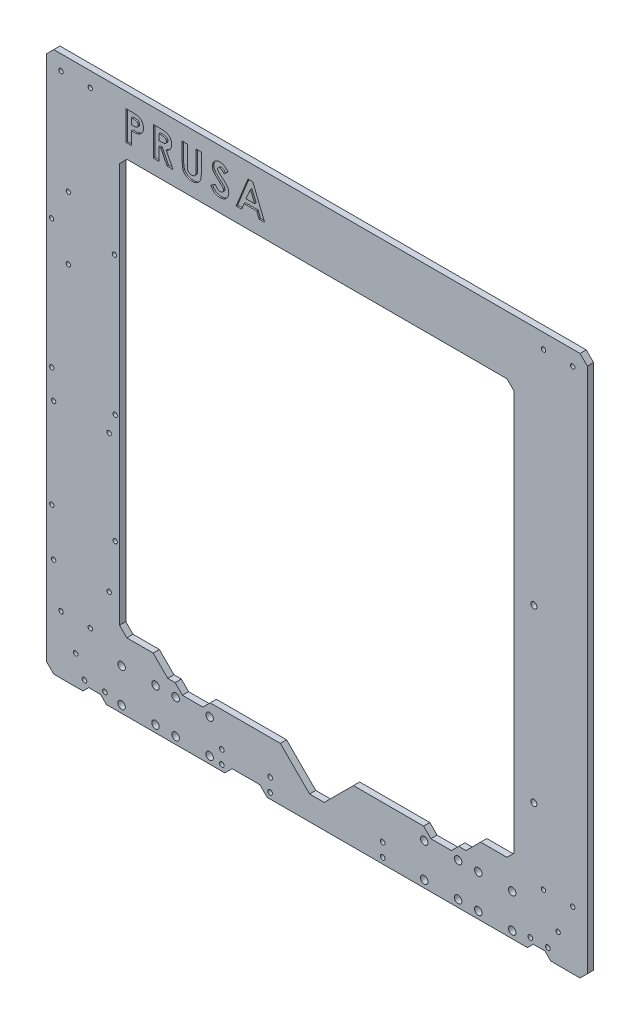
SolidWorks part; units mm, degrees
material "6063-O, Extruded Rod (SS)"
ref_plane "Front Plane" through (0, 0, 0) normal (0, 0, 1) x (1, 0, 0)
ref_plane "Top Plane" through (0, 0, 0) normal (0, 1, 0) x (1, 0, 0)
ref_plane "Right Plane" through (0, 0, 0) normal (1, 0, 0) x (0, 0, -1)
sketch "Sketch1" plane through (0, 0, 0) normal (0, 0, 1) x (1, 0, 0)
  line L0 (162, 177.023) -> (141.977, 157)
  line L1 (141.977, 157) -> (125, 157)
  line L2 (125, 157) -> (101.5, 180.5)
  line L3 (101.5, 189.5) -> (125, 213)
  line L4 (125, 213) -> (141.977, 213)
  line L5 (141.977, 213) -> (162, 192.977)
  line L6 (251.5, 210.0147) -> (240.9853, 220.5294)
  line L7 (240.9853, 220.5294) -> (224.0147, 220.5294)
  line L8 (224.0147, 220.5294) -> (197, 193.5147)
  line L9 (197, 176.4853) -> (224.0147, 149.4706)
  line L10 (224.0147, 149.4706) -> (240.9853, 149.4706)
  line L11 (240.9853, 149.4706) -> (251.5, 159.9853)
  line L12 (184.4001, 296) -> (225.4001, 255)
  line L13 (225.4001, 255) -> (241.5147, 255)
  line L14 (241.5147, 255) -> (282.5147, 296)
  line L15 (282.5147, 296) -> (287.4852, 296)
  line L16 (287.4852, 296) -> (291, 292.4852)
  line L17 (291, 292.4852) -> (291, 287.5147)
  line L18 (291, 287.5147) -> (253, 249.5147)
  line L19 (253, 249.5147) -> (253, 226.667)
  line L20 (253, 226.667) -> (291, 188.667)
  line L21 (291, 188.667) -> (291, 181.333)
  line L22 (291, 181.333) -> (253, 143.333)
  line L23 (253, 143.333) -> (253, 120.4853)
  line L24 (253, 120.4853) -> (291, 82.4853)
  line L25 (291, 82.4853) -> (291, 77.5148)
  line L26 (291, 77.5148) -> (287.4852, 74)
  line L27 (287.4852, 74) -> (282.5147, 74)
  line L28 (282.5147, 74) -> (241.5147, 115)
  line L29 (241.5147, 115) -> (225.4001, 115)
  line L30 (225.4001, 115) -> (184.4001, 74)
  line L31 (184.4001, 74) -> (175.5999, 74)
  line L32 (175.5999, 74) -> (134.5999, 115)
  line L33 (134.5999, 115) -> (113.4853, 115)
  line L34 (113.4853, 115) -> (72.4853, 74)
  line L35 (72.4853, 74) -> (67.5148, 74)
  line L36 (67.5148, 74) -> (64, 77.5148)
  line L37 (64, 77.5148) -> (64, 82.4853)
  line L38 (64, 82.4853) -> (91, 109.4853)
  line L39 (91, 109.4853) -> (91, 123)
  line L40 (91, 123) -> (81.5, 132.5)
  line L41 (81.5, 132.5) -> (81.5, 163.7609)
  line L42 (81.5, 163.7609) -> (64, 181.2609)
  line L43 (64, 188.7391) -> (81.5, 206.2391)
  line L44 (81.5, 206.2391) -> (81.5, 237.5)
  line L45 (81.5, 237.5) -> (91, 247)
  line L46 (91, 247) -> (91, 260.5147)
  line L47 (91, 260.5147) -> (64, 287.5147)
  line L48 (64, 287.5147) -> (64, 292.4852)
  line L49 (64, 292.4852) -> (67.5148, 296)
  line L50 (67.5148, 296) -> (72.4853, 296)
  line L51 (72.4853, 296) -> (113.4853, 255)
  line L52 (113.4853, 255) -> (134.5999, 255)
  line L53 (134.5999, 255) -> (175.5999, 296)
  line L54 (175.5999, 296) -> (184.4001, 296)
  line L55 (143, 246.4158) -> (143, 229.5663)
  line L56 (143, 229.5663) -> (159.5663, 213)
  line L57 (159.5663, 213) -> (199.5147, 213)
  line L58 (199.5147, 213) -> (216, 229.4853)
  line L59 (216, 229.4853) -> (216, 247.4296)
  line L60 (216, 247.4296) -> (183.6826, 279.747)
  line L61 (183.6826, 279.747) -> (176.3174, 279.7332)
  line L62 (176.3174, 279.7332) -> (143, 246.4158)
  line L63 (143, 123.5842) -> (143, 140.4337)
  line L64 (143, 140.4337) -> (159.5663, 157)
  line L65 (159.5663, 157) -> (199.5147, 157)
  line L66 (199.5147, 157) -> (216, 140.5147)
  line L67 (216, 140.5147) -> (216, 122.5704)
  line L68 (216, 122.5704) -> (183.6826, 90.253)
  line L69 (183.6826, 90.253) -> (176.3174, 90.2668)
  line L70 (176.3174, 90.2668) -> (143, 123.5842)
  line L71 (101.5, 226.75) -> (101.5, 213.25)
  line L72 (271.5, 191.75) -> (271.5, 178.25)
  line L73 (101.5, 156.75) -> (101.5, 143.25)
  line L74 (91.5, 226.75) -> (91.5, 213.25)
  line L75 (261.5, 191.75) -> (261.5, 178.25)
  line L76 (91.5, 156.75) -> (91.5, 143.25)
  line L77 (93.6792, 358.4107) -> (93.6792, 347.8262)
  line L78 (93.6792, 347.8262) -> (93.9406, 345.7354)
  line L79 (93.9406, 345.7354) -> (94.4633, 344.2327)
  line L80 (94.4633, 344.2327) -> (95.182, 343.1873)
  line L81 (95.182, 343.1873) -> (96.1846, 341.9648)
  line L82 (96.1846, 341.9648) -> (97.8105, 341.4329)
  line L83 (97.8105, 341.4329) -> (99.6248, 341.0966)
  line L84 (99.6248, 341.0966) -> (101.977, 341.3579)
  line L85 (101.977, 341.3579) -> (104.0024, 342.4033)
  line L86 (104.0024, 342.4033) -> (105.1131, 344.2327)
  line L87 (105.1131, 344.2327) -> (105.5705, 346.7155)
  line L88 (105.5705, 346.7155) -> (105.5705, 349.1983)
  line L89 (105.5705, 349.1983) -> (105.5705, 358.4107)
  line L90 (79.8932, 349.3289) -> (80.0892, 349.3289)
  line L91 (80.0892, 349.3289) -> (81.0039, 348.8063)
  line L92 (81.0039, 348.8063) -> (82.0493, 347.4342)
  line L93 (82.0493, 347.4342) -> (86.4922, 341.0966)
  line L94 (73.5556, 341.1619) -> (73.5556, 358.4107)
  line L95 (73.5556, 358.4107) -> (80.6119, 358.4107)
  line L96 (80.6119, 358.4107) -> (82.768, 357.7574)
  line L97 (82.768, 357.7574) -> (83.8134, 356.7773)
  line L98 (83.8134, 356.7773) -> (84.5321, 355.4706)
  line L99 (84.5321, 355.4706) -> (84.8588, 353.7065)
  line L100 (84.8588, 353.7065) -> (84.5321, 352.0078)
  line L101 (84.5321, 352.0078) -> (83.6827, 350.5703)
  line L102 (83.6827, 350.5703) -> (82.5067, 349.8517)
  line L103 (82.5067, 349.8517) -> (81.3306, 349.525)
  line L104 (81.3306, 349.525) -> (79.8932, 349.3289)
  line L105 (79.8932, 349.3289) -> (78.1291, 349.3289)
  line L106 (78.1291, 349.3289) -> (73.5556, 349.3289)
  line L107 (113.0897, 345.4442) -> (114.2004, 343.4842)
  line L108 (114.2004, 343.4842) -> (116.6178, 341.8507)
  line L109 (116.6178, 341.8507) -> (118.9699, 341.1974)
  line L110 (118.9699, 341.1974) -> (122.4328, 341.7201)
  line L111 (122.4328, 341.7201) -> (124.0662, 343.0268)
  line L112 (124.0662, 343.0268) -> (125.2422, 345.1176)
  line L113 (125.2422, 345.1176) -> (125.2422, 346.359)
  line L114 (125.2422, 346.359) -> (124.9156, 347.4697)
  line L115 (124.9156, 347.4697) -> (123.7395, 348.7764)
  line L116 (123.7395, 348.7764) -> (122.5635, 349.2991)
  line L117 (122.5635, 349.2991) -> (116.7485, 351.0632)
  line L118 (116.7485, 351.0632) -> (115.0497, 352.1739)
  line L119 (115.0497, 352.1739) -> (114.0044, 353.4153)
  line L120 (114.0044, 353.4153) -> (113.8737, 354.5914)
  line L121 (113.8737, 354.5914) -> (114.135, 356.3554)
  line L122 (114.135, 356.3554) -> (115.3764, 357.6622)
  line L123 (115.3764, 357.6622) -> (117.4672, 358.4462)
  line L124 (117.4672, 358.4462) -> (120.0807, 358.5769)
  line L125 (120.0807, 358.5769) -> (122.8248, 357.8582)
  line L126 (122.8248, 357.8582) -> (123.9355, 356.8128)
  line L127 (123.9355, 356.8128) -> (124.3929, 355.5714)
  line L128 (130.9954, 341.0312) -> (137.9864, 358.5414)
  line L129 (137.9864, 358.5414) -> (139.0972, 358.5414)
  line L130 (139.0972, 358.5414) -> (145.9575, 341.0312)
  line L131 (143.9343, 346.1951) -> (133.0803, 346.1927)
  line L132 (55, 341.1619) -> (55, 358.4107)
  line L133 (55, 358.4107) -> (62.0563, 358.4107)
  line L134 (62.0563, 358.4107) -> (64.2125, 357.7574)
  line L135 (64.2125, 357.7574) -> (65.2578, 356.7773)
  line L136 (65.2578, 356.7773) -> (65.9765, 355.4706)
  line L137 (65.9765, 355.4706) -> (66.3032, 353.7065)
  line L138 (66.3032, 353.7065) -> (65.9765, 352.0078)
  line L139 (65.9765, 352.0078) -> (65.1272, 350.5703)
  line L140 (65.1272, 350.5703) -> (63.9511, 349.8517)
  line L141 (63.9511, 349.8517) -> (62.7751, 349.525)
  line L142 (62.7751, 349.525) -> (61.3376, 349.3289)
  line L143 (61.3376, 349.3289) -> (59.5735, 349.3289)
  line L144 (59.5735, 349.3289) -> (55, 349.3289)
  line L145 (251.5, 210.0147) -> (251.5, 159.9853)
  line L146 (197, 193.5147) -> (197, 176.4853)
  line L147 (64, 188.7391) -> (64, 181.2609)
  line L148 (101.5, 189.5) -> (101.5, 180.5)
  line L149 (162, 192.977) -> (162, 177.023)
  line L150 (102.1, 142.75) -> (102, 142.75)
  line L151 (272.1, 177.75) -> (272, 177.75)
  line L152 (102.1, 212.75) -> (102, 212.75)
  line L153 (90.9, 142.75) -> (91, 142.75)
  line L154 (260.9, 177.75) -> (261, 177.75)
  line L155 (90.9, 212.75) -> (91, 212.75)
  line L156 (102, 142.75) -> (101.5, 143.25)
  line L157 (272, 177.75) -> (271.5, 178.25)
  line L158 (102, 212.75) -> (101.5, 213.25)
  line L159 (91, 142.75) -> (91.5, 143.25)
  line L160 (261, 177.75) -> (261.5, 178.25)
  line L161 (91, 212.75) -> (91.5, 213.25)
  line L162 (102.1, 157.25) -> (102, 157.25)
  line L163 (272.1, 192.25) -> (272, 192.25)
  line L164 (102.1, 227.25) -> (102, 227.25)
  line L165 (90.9, 157.25) -> (91, 157.25)
  line L166 (260.9, 192.25) -> (261, 192.25)
  line L167 (90.9, 227.25) -> (91, 227.25)
  line L168 (101.5, 156.75) -> (102, 157.25)
  line L169 (271.5, 191.75) -> (272, 192.25)
  line L170 (101.5, 226.75) -> (102, 227.25)
  line L171 (91.5, 156.75) -> (91, 157.25)
  line L172 (261.5, 191.75) -> (261, 192.25)
  line L173 (91.5, 226.75) -> (91, 227.25)
  line L174 (90.9, 163.25) -> (102.1, 163.25)
  line L175 (260.9, 198.25) -> (272.1, 198.25)
  line L176 (90.9, 233.25) -> (102.1, 233.25)
  line L177 (90.9, 136.75) -> (102.1, 136.75)
  line L178 (260.9, 171.75) -> (272.1, 171.75)
  line L179 (90.9, 206.75) -> (102.1, 206.75)
  arc A0 (102.1, 206.75) -> (102.1, 212.75) centre (102.1, 209.75) ccw
  arc A1 (272.1, 171.75) -> (272.1, 177.75) centre (272.1, 174.75) ccw
  arc A2 (102.1, 136.75) -> (102.1, 142.75) centre (102.1, 139.75) ccw
  arc A3 (90.9, 142.75) -> (90.9, 136.75) centre (90.9, 139.75) ccw
  arc A4 (90.9, 212.75) -> (90.9, 206.75) centre (90.9, 209.75) ccw
  arc A5 (260.9, 177.75) -> (260.9, 171.75) centre (260.9, 174.75) ccw
  arc A6 (102.1, 157.25) -> (102.1, 163.25) centre (102.1, 160.25) ccw
  arc A7 (102.1, 227.25) -> (102.1, 233.25) centre (102.1, 230.25) ccw
  arc A8 (272.1, 192.25) -> (272.1, 198.25) centre (272.1, 195.25) ccw
  arc A9 (90.9, 163.25) -> (90.9, 157.25) centre (90.9, 160.25) ccw
  arc A10 (260.9, 198.25) -> (260.9, 192.25) centre (260.9, 195.25) ccw
  arc A11 (90.9, 233.25) -> (90.9, 227.25) centre (90.9, 230.25) ccw
  circle A12 centre (318.6, 4.9) radius 2.55
  circle A13 centre (318.6, 28.1) radius 2.55
  circle A14 centre (295.4, 28.1) radius 2.55
  circle A15 centre (295.4, 4.9) radius 2.55
  circle A16 centre (281.6, 4.9) radius 2.55
  circle A17 centre (258.4, 4.9) radius 2.55
  circle A18 centre (258.4, 28.1) radius 2.55
  circle A19 centre (281.6, 28.1) radius 2.55
  circle A20 centre (111.6, 4.9) radius 2.55
  circle A21 centre (111.6, 28.1) radius 2.55
  circle A22 centre (88.4, 28.1) radius 2.55
  circle A23 centre (88.4, 4.9) radius 2.55
  circle A24 centre (74.6, 4.9) radius 2.55
  circle A25 centre (74.6, 28.1) radius 2.55
  circle A26 centre (51.4, 28.1) radius 2.55
  circle A27 centre (51.4, 4.9) radius 2.55
  circle A28 centre (360, 39.8) radius 1.5
  circle A29 centre (10, 39.8) radius 1.5
  circle A30 centre (340, 359.8) radius 1.5
  circle A31 centre (30, 39.8) radius 1.5
  circle A32 centre (42.9, 67.8) radius 1.5
  circle A33 centre (340, 39.8) radius 1.5
  circle A34 centre (10, 359.8) radius 1.5
  circle A35 centre (350, 19.8) radius 1.5
  circle A36 centre (47, 99.8) radius 1.5
  circle A37 centre (3.7, 181.1) radius 1.5
  circle A38 centre (20, 19.8) radius 1.5
  circle A39 centre (4.9, 67.8) radius 1.5
  circle A40 centre (360, 359.8) radius 1.5
  circle A41 centre (42.9, 161.8) radius 1.5
  circle A42 centre (3.7, 99.8) radius 1.5
  circle A43 centre (30, 359.8) radius 1.5
  circle A44 centre (47, 174.7) radius 1.5
  circle A45 centre (4.9, 161.8) radius 1.5
  circle A46 centre (46.5, 269.3) radius 1.5
  circle A47 centre (15, 247.8) radius 1.5
  circle A48 centre (3.5, 269.3) radius 1.5
  circle A49 centre (15, 290.8) radius 1.5
  circle A50 centre (180, 80) radius 1.5
  circle A51 centre (180, 290) radius 1.5
  circle A52 centre (285, 80) radius 1.5
  circle A53 centre (70, 290) radius 1.5
  circle A54 centre (285, 290) radius 1.5
  circle A55 centre (70, 185) radius 1.5
  circle A56 centre (180, 185) radius 1.5
  circle A57 centre (285, 185) radius 1.5
  circle A58 centre (256.5, 185) radius 1.6
  circle A59 centre (276.5, 185) radius 1.6
  circle A60 centre (106.5, 220) radius 1.6
  circle A61 centre (106.5, 150) radius 1.6
  circle A62 centre (86.5, 220) radius 1.6
  circle A63 centre (86.5, 150) radius 1.6
  circle A64 centre (70, 80) radius 1.5
  circle A65 centre (181.5, 165.5) radius 1.5
  circle A66 centre (181.5, 204.5) radius 1.5
  circle A67 centre (40, 7) radius 1.6
  circle A68 centre (331, 7) radius 1.6
  circle A69 centre (343, 7) radius 1.6
  circle A70 centre (120, 13) radius 1.6
  circle A71 centre (120, 4) radius 1.6
  circle A72 centre (230, 13) radius 1.6
  circle A73 centre (230, 4) radius 1.6
  circle A74 centre (333.4, 205) radius 2.1
  circle A75 centre (333.4, 88) radius 2.1
  circle A76 centre (26, 7) radius 1.6
  circle A77 centre (153, 13) radius 1.6
  circle A78 centre (153, 4) radius 1.6
  spline S0 degree 2 poles (5, 370) (2.5, 367.5) (0, 365) knots 1472.868668 1472.868668 1472.868668 1479.939736 1479.939736 1479.939736
  spline S1 degree 2 poles (365, 370) (185, 370) (5, 370) knots 1112.868668 1112.868668 1112.868668 1472.868668 1472.868668 1472.868668
  spline S2 degree 2 poles (370, 365) (367.5, 367.5) (365, 370) knots 1105.7976 1105.7976 1105.7976 1112.868668 1112.868668 1112.868668
  spline S3 degree 2 poles (370, 5) (370, 185) (370, 365) knots 745.7976 745.7976 745.7976 1105.7976 1105.7976 1105.7976
  spline S4 degree 2 poles (365, 0) (367.5, 2.5) (370, 5) knots 738.726533 738.726533 738.726533 745.7976 745.7976 745.7976
  spline S5 degree 2 poles (345, 0) (355, 0) (365, 0) knots 718.726533 718.726533 718.726533 738.726533 738.726533 738.726533
  spline S6 degree 2 poles (341, 4) (343, 2) (345, 0) knots 710.241251 710.241251 710.241251 718.726533 718.726533 718.726533
  spline S7 degree 2 poles (333, 4) (337, 4) (341, 4) knots 704.241251 704.241251 704.241251 710.241251 710.241251 710.241251
  spline S8 degree 2 poles (329, 0) (331, 2) (333, 4) knots 698.584397 698.584397 698.584397 704.241251 704.241251 704.241251
  spline S9 degree 2 poles (151, 0) (240, 0) (329, 0) knots 507.584397 507.584397 507.584397 698.584397 698.584397 698.584397
  spline S10 degree 2 poles (146, 5) (148.5, 2.5) (151, 0) knots 501.927543 501.927543 501.927543 507.584397 507.584397 507.584397
  spline S11 degree 2 poles (127, 5) (136.5, 5) (146, 5) knots 487.927543 487.927543 487.927543 501.927543 501.927543 501.927543
  spline S12 degree 2 poles (122, 0) (124.5, 2.5) (127, 5) knots 482.270688 482.270688 482.270688 487.927543 487.927543 487.927543
  spline S13 degree 2 poles (41, 0) (81.5, 0) (122, 0) knots 407.270688 407.270688 407.270688 482.270688 482.270688 482.270688
  spline S14 degree 2 poles (37, 4) (39, 2) (41, 0) knots 401.613834 401.613834 401.613834 407.270688 407.270688 407.270688
  spline S15 degree 2 poles (29, 4) (33, 4) (37, 4) knots 395.613834 395.613834 395.613834 401.613834 401.613834 401.613834
  spline S16 degree 2 poles (25, 0) (27, 2) (29, 4) knots 387.128553 387.128553 387.128553 395.613834 395.613834 395.613834
  spline S17 degree 2 poles (5, 0) (15, 0) (25, 0) knots 367.128553 367.128553 367.128553 387.128553 387.128553 387.128553
  spline S18 degree 2 poles (0, 5) (2.5, 2.5) (5, 0) knots 360.191742 360.191742 360.191742 367.128553 367.128553 367.128553
  spline S19 degree 2 poles (0, 365) (0, 185) (0, 5) knots 0 0 0 360.191742 360.191742 360.191742
  spline S20 degree 2 poles (93, 31.5) (100, 31.5) (107, 31.5) knots 1110.421356 1110.421356 1110.421356 1117.046356 1117.046356 1117.046356
  spline S21 degree 2 poles (88, 36.5) (90.5, 34) (93, 31.5) knots 1103.350288 1103.350288 1103.350288 1110.421356 1110.421356 1110.421356
  spline S22 degree 2 poles (83, 36.5) (85.5, 36.5) (88, 36.5) knots 1098.350288 1098.350288 1098.350288 1103.350288 1103.350288 1103.350288
  spline S23 degree 2 poles (73, 46.5) (78, 41.5) (83, 36.5) knots 1084.208153 1084.208153 1084.208153 1098.350288 1098.350288 1098.350288
  spline S24 degree 2 poles (55, 46.5) (64, 46.5) (73, 46.5) knots 1066.208153 1066.208153 1066.208153 1084.208153 1084.208153 1084.208153
  spline S25 degree 2 poles (50, 51.5) (52.5, 49) (55, 46.5) knots 1059.137085 1059.137085 1059.137085 1066.208153 1066.208153 1066.208153
  spline S26 degree 2 poles (50, 325) (50, 188.25) (50, 51.5) knots 787.637085 787.637085 787.637085 1059.137085 1059.137085 1059.137085
  spline S27 degree 2 poles (55, 330) (52.5, 327.5) (50, 325) knots 780.566017 780.566017 780.566017 787.637085 787.637085 787.637085
  spline S28 degree 2 poles (315, 330) (185, 330) (55, 330) knots 520.566017 520.566017 520.566017 780.566017 780.566017 780.566017
  spline S29 degree 2 poles (320, 325) (317.5, 327.5) (315, 330) knots 513.494949 513.494949 513.494949 520.566017 520.566017 520.566017
  spline S30 degree 2 poles (320, 51.5) (320, 188.25) (320, 325) knots 241.994949 241.994949 241.994949 513.494949 513.494949 513.494949
  spline S31 degree 2 poles (315, 46.5) (317.5, 49) (320, 51.5) knots 234.923882 234.923882 234.923882 241.994949 241.994949 241.994949
  spline S32 degree 2 poles (297, 46.5) (306, 46.5) (315, 46.5) knots 216.923882 216.923882 216.923882 234.923882 234.923882 234.923882
  spline S33 degree 2 poles (287, 36.5) (292, 41.5) (297, 46.5) knots 202.781746 202.781746 202.781746 216.923882 216.923882 216.923882
  spline S34 degree 2 poles (282, 36.5) (284.5, 36.5) (287, 36.5) knots 197.781746 197.781746 197.781746 202.781746 202.781746 202.781746
  spline S35 degree 2 poles (277, 31.5) (279.5, 34) (282, 36.5) knots 190.710678 190.710678 190.710678 197.781746 197.781746 197.781746
  spline S36 degree 2 poles (263, 31.5) (264, 31.5) (265, 31.5) (270, 31.5) (275, 31.5) (276, 31.5) (277, 31.5) knots 176.710678 176.710678 176.710678 178.710678 178.710678 188.710678 188.710678 190.710678 190.710678 190.710678
  spline S37 degree 2 poles (258, 36.5) (260.5, 34) (263, 31.5) knots 169.63961 169.63961 169.63961 176.710678 176.710678 176.710678
  spline S38 degree 2 poles (210, 36.5) (211.75, 36.5) (213.5, 36.5) (235.75, 36.5) (258, 36.5) knots 121.63961 121.63961 121.63961 125.13961 125.13961 169.63961 169.63961 169.63961
  spline S39 degree 2 poles (190, 16.5) (200, 26.5) (210, 36.5) knots 93.355339 93.355339 93.355339 121.63961 121.63961 121.63961
  spline S40 degree 2 poles (180, 16.5) (185, 16.5) (190, 16.5) knots 83.355339 83.355339 83.355339 93.355339 93.355339 93.355339
  spline S41 degree 2 poles (160, 36.5) (170, 26.5) (180, 16.5) knots 55.071068 55.071068 55.071068 83.355339 83.355339 83.355339
  spline S42 degree 2 poles (112, 36.5) (134.25, 36.5) (156.5, 36.5) (158.25, 36.5) (160, 36.5) knots 7.071068 7.071068 7.071068 51.571068 51.571068 55.071068 55.071068 55.071068
  spline S43 degree 2 poles (107, 31.5) (109.5, 34) (112, 36.5) knots 0 0 0 7.071068 7.071068 7.071068
extrude "Boss-Extrude1" add sketch "Sketch1" along normal blind 4.25
sketch "Sketch2" plane through (0, 0, 4.25) normal (0, 0, 1) x (1, 0, 0)
  text T0 "<b>PRUSA</b>" font "Century Gothic" height 20
extrude "Cut-Extrude1" cut sketch "Sketch2" against normal blind 1
